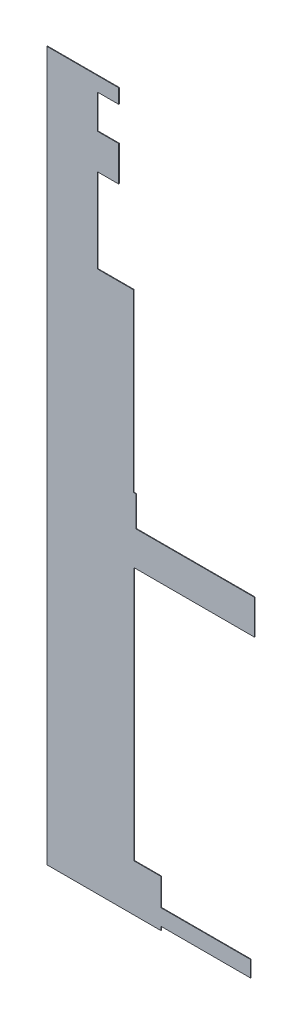
SolidWorks part; units mm, degrees
ref_plane "前视基准面" through (0, 0, 0) normal (0, 0, 1) x (1, 0, 0)
ref_plane "上视基准面" through (0, 0, 0) normal (0, 1, 0) x (1, 0, 0)
ref_plane "右视基准面" through (0, 0, 0) normal (1, 0, 0) x (0, 0, -1)
ref_plane "基准面4"
sketch "草图1" plane through (0, 0, 42) normal (0, 0, 1) x (1, 0, 0)
  line L0 (83.4, -1092.3) -> (83.4, -1117.3)
  line L1 (83.4, -1117.3) -> (98.6, -1117.3)
  line L2 (98.6, -1117.3) -> (98.6, -1092.3)
  line L3 (98.6, -1092.3) -> (83.4, -1092.3)
  line L4 (98.6, -1092.3) -> (98.6, -1117.3)
  line L5 (98.6, -1117.3) -> (114.5, -1117.3)
  line L6 (114.5, -1117.3) -> (114.5, -1092.3)
  line L7 (114.5, -1092.3) -> (98.6, -1092.3)
  line L8 (143.4, -837.8) -> (83.4, -837.8)
  line L9 (83.4, -837.8) -> (83.4, -893.6)
  line L10 (83.4, -893.6) -> (143.4, -893.6)
  line L11 (143.4, -893.6) -> (143.4, -837.8)
  line L12 (0, -782.9) -> (0, -839.5)
  line L13 (0, -839.5) -> (60, -839.5)
  line L14 (60, -839.5) -> (60, -782.9)
  line L15 (60, -782.9) -> (0, -782.9)
  line L16 (0, -276.5) -> (0, -335.9)
  line L17 (0, -335.9) -> (60, -335.9)
  line L18 (60, -335.9) -> (60, -276.5)
  line L19 (60, -276.5) -> (0, -276.5)
  line L20 (188.1, -1163.6) -> (336, -1163.6)
  line L21 (336, -1163.6) -> (336, -1137.1)
  line L22 (336, -1137.1) -> (188.1, -1137.1)
  line L23 (188.1, -1137.1) -> (188.1, -1163.6)
  line L24 (60, -1169.8) -> (60, -1091.2)
  line L25 (60, -1091.2) -> (0, -1091.2)
  line L26 (0, -1091.2) -> (0, -1169.8)
  line L27 (0, -1169.8) -> (60, -1169.8)
  line L28 (0, 0) -> (0, -80.6)
  line L29 (0, -80.6) -> (60, -80.6)
  line L30 (60, -80.6) -> (60, 0)
  line L31 (60, 0) -> (0, 0)
  line L32 (143.4, -673.2) -> (83.4, -673.2)
  line L33 (83.4, -673.2) -> (83.4, -754.3)
  line L34 (83.4, -754.3) -> (143.4, -754.3)
  line L35 (143.4, -754.3) -> (143.4, -673.2)
  line L36 (142.9, -379.5) -> (83.4, -379.5)
  line L37 (83.4, -379.5) -> (83.4, -463)
  line L38 (83.4, -463) -> (142.9, -463)
  line L39 (142.9, -463) -> (142.9, -379.5)
  line L40 (0, -1007.7) -> (0, -1091.2)
  line L41 (0, -1091.2) -> (60, -1091.2)
  line L42 (60, -1091.2) -> (60, -1007.7)
  line L43 (60, -1007.7) -> (0, -1007.7)
  line L44 (83.4, -754.3) -> (83.4, -837.8)
  line L45 (83.4, -837.8) -> (143.4, -837.8)
  line L46 (143.4, -837.8) -> (143.4, -754.3)
  line L47 (143.4, -754.3) -> (83.4, -754.3)
  line L48 (0, -923.6) -> (0, -1007.7)
  line L49 (0, -1007.7) -> (60, -1007.7)
  line L50 (60, -1007.7) -> (60, -923.6)
  line L51 (60, -923.6) -> (0, -923.6)
  line L52 (0, -839.5) -> (0, -923.6)
  line L53 (0, -923.6) -> (60, -923.6)
  line L54 (60, -923.6) -> (60, -839.5)
  line L55 (60, -839.5) -> (0, -839.5)
  line L56 (0, -191.9) -> (0, -276.5)
  line L57 (0, -276.5) -> (60, -276.5)
  line L58 (60, -276.5) -> (60, -191.9)
  line L59 (60, -191.9) -> (0, -191.9)
  line L60 (0, -335.9) -> (0, -420.6)
  line L61 (0, -420.6) -> (60, -420.6)
  line L62 (60, -420.6) -> (60, -335.9)
  line L63 (60, -335.9) -> (0, -335.9)
  line L64 (83.4, -893.6) -> (83.4, -978.3)
  line L65 (83.4, -978.3) -> (143.4, -978.3)
  line L66 (143.4, -978.3) -> (143.4, -893.6)
  line L67 (143.4, -893.6) -> (83.4, -893.6)
  line L68 (83.4, -276.5) -> (83.4, -379.5)
  line L69 (83.4, -379.5) -> (142.9, -379.5)
  line L70 (142.9, -379.5) -> (142.9, -276.5)
  line L71 (142.9, -276.5) -> (83.4, -276.5)
  line L72 (142.9, -463) -> (83.4, -463)
  line L73 (83.4, -463) -> (83.4, -566.2)
  line L74 (83.4, -566.2) -> (142.9, -566.2)
  line L75 (142.9, -566.2) -> (142.9, -463)
  line L76 (0, -677.8) -> (0, -782.9)
  line L77 (0, -782.9) -> (60, -782.9)
  line L78 (60, -782.9) -> (60, -677.8)
  line L79 (60, -677.8) -> (0, -677.8)
  line L80 (0, -80.6) -> (0, -191.9)
  line L81 (0, -191.9) -> (60, -191.9)
  line L82 (60, -191.9) -> (60, -80.6)
  line L83 (60, -80.6) -> (0, -80.6)
  line L84 (83.4, -1092.3) -> (98.6, -1092.3)
  line L85 (98.6, -1092.3) -> (114.5, -1092.3)
  line L86 (114.5, -1092.3) -> (143.4, -1092.3)
  line L87 (143.4, -1092.3) -> (143.4, -978.3)
  line L88 (143.4, -978.3) -> (83.4, -978.3)
  line L89 (83.4, -978.3) -> (83.4, -1092.3)
  line L90 (0, -550.6) -> (0, -677.8)
  line L91 (0, -677.8) -> (60, -677.8)
  line L92 (60, -677.8) -> (60, -550.6)
  line L93 (60, -550.6) -> (0, -550.6)
  line L94 (0, -420.6) -> (0, -550.6)
  line L95 (0, -550.6) -> (60, -550.6)
  line L96 (60, -550.6) -> (60, -420.6)
  line L97 (60, -420.6) -> (0, -420.6)
  line L98 (166.2, -1092.3) -> (143.4, -1092.3)
  line L99 (143.4, -1092.3) -> (114.5, -1092.3)
  line L100 (114.5, -1092.3) -> (114.5, -1117.3)
  line L101 (114.5, -1117.3) -> (98.6, -1117.3)
  line L102 (98.6, -1117.3) -> (83.4, -1117.3)
  line L103 (83.4, -1117.3) -> (83.4, -1092.3)
  line L104 (83.4, -1092.3) -> (83.4, -978.3)
  line L105 (83.4, -978.3) -> (83.4, -893.6)
  line L106 (83.4, -893.6) -> (83.4, -837.8)
  line L107 (83.4, -837.8) -> (83.4, -754.3)
  line L108 (83.4, -754.3) -> (83.4, -673.2)
  line L109 (83.4, -673.2) -> (143.4, -673.2)
  line L110 (143.4, -673.2) -> (342.5, -673.2)
  line L111 (342.5, -673.2) -> (342.5, -616.2)
  line L112 (342.5, -616.2) -> (192.5, -616.2)
  line L113 (192.5, -616.2) -> (146.7, -616.2)
  line L114 (146.7, -616.2) -> (146.7, -566.2)
  line L115 (146.7, -566.2) -> (142.9, -566.2)
  line L116 (142.9, -566.2) -> (83.4, -566.2)
  line L117 (83.4, -566.2) -> (83.4, -463)
  line L118 (83.4, -463) -> (83.4, -379.5)
  line L119 (83.4, -379.5) -> (83.4, -276.5)
  line L120 (83.4, -276.5) -> (83.4, -137.6)
  line L121 (83.4, -137.6) -> (118.4, -137.6)
  line L122 (118.4, -137.6) -> (118.4, -79.7)
  line L123 (118.4, -79.7) -> (83.4, -79.7)
  line L124 (83.4, -79.7) -> (83.4, -23.7)
  line L125 (83.4, -23.7) -> (118.4, -23.7)
  line L126 (118.4, -23.7) -> (118.4, 0)
  line L127 (118.4, 0) -> (60, 0)
  line L128 (60, 0) -> (60, -80.6)
  line L129 (60, -80.6) -> (60, -191.9)
  line L130 (60, -191.9) -> (60, -276.5)
  line L131 (60, -276.5) -> (60, -335.9)
  line L132 (60, -335.9) -> (60, -420.6)
  line L133 (60, -420.6) -> (60, -550.6)
  line L134 (60, -550.6) -> (60, -677.8)
  line L135 (60, -677.8) -> (60, -782.9)
  line L136 (60, -782.9) -> (60, -839.5)
  line L137 (60, -839.5) -> (60, -923.6)
  line L138 (60, -923.6) -> (60, -1007.7)
  line L139 (60, -1007.7) -> (60, -1091.2)
  line L140 (60, -1091.2) -> (60, -1169.8)
  line L141 (60, -1169.8) -> (188.1, -1169.8)
  line L142 (188.1, -1169.8) -> (188.1, -1163.6)
  line L143 (188.1, -1163.6) -> (188.1, -1137.1)
  line L144 (188.1, -1137.1) -> (188.1, -1117.3)
  line L145 (188.1, -1117.3) -> (188.1, -1092.3)
  line L146 (188.1, -1092.3) -> (166.2, -1092.3)
  dimension "D1" = 60
  dimension "D2" = 80.6
  dimension "D3" = 111.3
  dimension "D4" = 84.6
  dimension "D5" = 59.4
  dimension "D6" = 84.7
  dimension "D7" = 130
  dimension "D8" = 127.2
  dimension "D9" = 105.1
  dimension "D10" = 56.6
  dimension "D11" = 84.1
  dimension "D12" = 84.1
  dimension "D13" = 83.5
  dimension "D14" = 78.6
  dimension "D15" = 58.4
  dimension "D16" = 23.7
  dimension "D17" = 35
  dimension "D18" = 56
  dimension "D19" = 57.9
  dimension "D20" = 35
  dimension "D21" = 138.9
  dimension "D22" = 59.5
  dimension "D23" = 103
  dimension "D24" = 83.5
  dimension "D25" = 103.2
  dimension "D26" = 59.5
  dimension "D27" = 3.8
  dimension "D28" = 50
  dimension "D29" = 45.8
  dimension "D30" = 150
  dimension "D31" = 57
  dimension "D32" = 199.1
  dimension "D33" = 60
  dimension "D34" = 81.1
  dimension "D35" = 83.5
  dimension "D36" = 55.8
  dimension "D37" = 84.7
  dimension "D38" = 90
  dimension "D39" = 128.1
  dimension "D40" = 15.2
  dimension "D41" = 15.9
  dimension "D42" = 147.9
  dimension "D43" = 6.2
  dimension "D44" = 26.5
extrude "拉伸1" add sketch "草图1" against normal blind 1 contours L2 L3 L0 L1 | L6 L7 L2 L5 | L10 L11 L8 L9 | L14 L15 L12 L13 | L18 L19 L16 L17 | L22 L23 L20 L21 | L26 L27 L24 L25 | L30 L31 L28 L29 | L34 L35 L32 L33 | L38 L39 L36 L37 | L42 L43 L40 L25 | L8 L46 L34 L44 | L50 L51 L48 L43 | L51 L54 L13 L52 | L58 L59 L56 L19 | L61 L62 L17 L60 | L65 L66 L10 L64 | L70 L71 L68 L36 | L74 L75 L38 L73 | L78 L79 L76 L15 | L59 L82 L29 L80 | L65 L89 L3 L7 L86 L87 | L92 L93 L90 L79 | L93 L96 L61 L94 | L145 L146 L98 L86 L6 L5 L1 L0 L89 L64 L9 L44 L33 L32 L110 L111 L112 L113 L114 L115 L74 L73 L37 L68 L120 L121 L122 L123 L124 L125 L126 L127 L30 L82 L58 L18 L62 L96 L92 L78 L14 L54 L50 L42 L24 L141 L142 L23 L144
